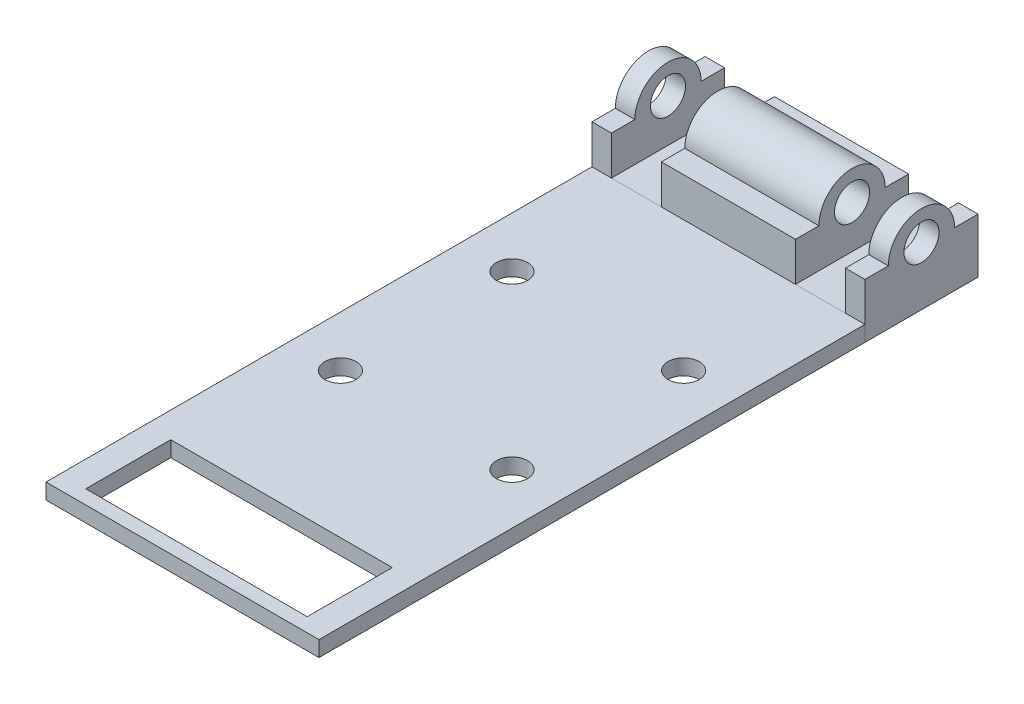
SolidWorks part; units mm, degrees
ref_plane "Front Plane" through (0, 0, 0) normal (0, 0, 1) x (1, 0, 0)
ref_plane "Top Plane" through (0, 0, 0) normal (0, 1, 0) x (1, 0, 0)
ref_plane "Right Plane" through (0, 0, 0) normal (1, 0, 0) x (0, 0, -1)
sketch "Sketch1" plane through (0, 0, 0) normal (1, 0, 0) x (0, 0, -1)
  line L0 (2.25, 1.5) -> (7.25, 1.5)
  line L1 (-2.25, -1.5) -> (2.25, -1.5)
  line L2 (-2.25, -1.5) -> (-2.25, 1.5)
  line L3 (-2.25, 1.5) -> (2.25, 1.5) construction
  line L4 (2.25, -1.5) -> (2.25, 1.5)
  line L5 (-2.25, -1.5) -> (2.25, 1.5) construction
  line L6 (-2.25, 1.5) -> (2.25, -1.5) construction
  line L7 (7.25, 1.5) -> (7.25, 8.5)
  line L8 (7.25, 8.5) -> (4.25, 8.5)
  line L9 (-2.25, 1.5) -> (-7.25, 1.5)
  line L10 (-7.25, 1.5) -> (-7.25, 8.5)
  line L11 (-7.25, 8.5) -> (-4.25, 8.5)
  line L12 (0, 1.5) -> (0, 9) construction
  line L13 (0, 11.25) -> (0, 12.75) construction
  circle A0 centre (0, 9) radius 2.25
  arc A1 (-4.25, 8.5) -> (4.25, 8.5) centre (0, 8.5) cw
  point P0 (0, 0)
  dimension "D10" = 4.5
  dimension "D11" = 1.5
  dimension "D1" = 3
  dimension "D2" = 4.5
  dimension "D3" = 5
  dimension "D4" = 5
  dimension "D5" = 7
  dimension "D6" = 7
  dimension "D7" = 3
  dimension "D8" = 3
  dimension "D9" = 7.5
extrude "Boss-Extrude1" add sketch "Sketch1" along normal mid plane 40
sketch "Sketch2" plane through (0, 0, 7.25) normal (0, 0, 1) x (1, 0, 0)
  line L0 (20, 12.75) -> (-20, 12.75) construction
  line L1 (-15, 12.75) -> (15, 12.75)
  line L2 (-15, 12.75) -> (-15, 3.5)
  line L3 (-15, 3.5) -> (15, 3.5)
  line L4 (15, 12.75) -> (15, 3.5)
  line L5 (-15, 12.75) -> (15, 3.5) construction
  line L6 (-15, 3.5) -> (15, 12.75) construction
  line L7 (20, 1.5) -> (-20, 1.5) construction
  line L8 (-20, 12.75) -> (-20, 8.5) construction
  line L9 (20, 8.5) -> (20, 12.75) construction
  point P4 (0, 8.125)
  dimension "D1" = 2
  dimension "D2" = 5
  dimension "D3" = 5
extrude "Cut-Extrude1" cut sketch "Sketch2" against normal through all
sketch "Sketch3" plane through (0, 0, 7.25) normal (0, 0, 1) x (1, 0, 0)
  line L1 (-20, 12.75) -> (-17.5, 12.75)
  line L2 (-20, 12.75) -> (-20, -1.5)
  line L3 (-20, -1.5) -> (-17.5, -1.5)
  line L4 (-17.5, 12.75) -> (-17.5, -1.5)
  line L5 (-20, 12.75) -> (-17.5, -1.5) construction
  line L6 (-20, -1.5) -> (-17.5, 12.75) construction
  line L7 (20, 12.75) -> (17.5, 12.75)
  line L8 (20, 12.75) -> (20, -1.5)
  line L9 (20, -1.5) -> (17.5, -1.5)
  line L10 (17.5, 12.75) -> (17.5, -1.5)
  line L11 (20, 12.75) -> (17.5, -1.5) construction
  line L12 (20, -1.5) -> (17.5, 12.75) construction
  line L13 (-15, 8.5) -> (-15, 12.75) construction
  line L14 (15, 12.75) -> (15, 8.5) construction
  line L15 (20, -1.5) -> (-20, -1.5) construction
  point P4 (-18.75, 5.625)
  point P10 (18.75, 5.625)
  dimension "D1" = 2.5
  dimension "D2" = 2.5
extrude "Cut-Extrude2" cut sketch "Sketch3" against normal through all
sketch "Sketch5" plane through (0, 0, 0) normal (1, 0, 0) x (0, 0, -1)
  line L5 (-4.25, 8.5) -> (-7.25, 8.5)
  line L6 (-7.25, 8.5) -> (-7.25, 3.5)
  line L7 (-7.25, 3.5) -> (7.25, 3.5)
  line L8 (7.25, 3.5) -> (7.25, 8.5)
  line L9 (7.25, 8.5) -> (4.25, 8.5)
  line L10 (-4.25, 8.5) -> (-7.25, 8.5)
  line L11 (-7.25, 8.5) -> (-7.25, 3.5)
  line L12 (-7.25, 3.5) -> (7.25, 3.5)
  line L13 (7.25, 3.5) -> (7.25, 8.5)
  line L14 (7.25, 8.5) -> (4.25, 8.5)
  circle A1 centre (0, 9) radius 2.25
  circle A2 centre (0, 9) radius 2.25
  arc A3 (4.25, 8.5) -> (-4.25, 8.5) centre (0, 8.5) ccw
  arc A4 (4.25, 8.5) -> (-4.25, 8.5) centre (0, 8.5) ccw
  dimension "D1" = 0
  dimension "D2" = 0
extrude "Boss-Extrude2" add sketch "Sketch5" against normal offset from surface 6.4 and the other way offset from surface (8.6 mm away) 6.4 up to face at (-15, 6.75, 0) other way up to face at (15, 9, -2.25)
sketch "Sketch6" plane through (-17.5, 0, 0) normal (-1, 0, 0) x (0, 0, 1)
  line L1 (-2.25, -1.5) -> (2.25, -1.5)
  line L2 (-2.25, -1.5) -> (-2.25, 1.5)
  line L3 (-2.25, 1.5) -> (2.25, 1.5)
  line L4 (2.25, -1.5) -> (2.25, 1.5)
  line L5 (-2.25, -1.5) -> (2.25, 1.5) construction
  line L6 (-2.25, 1.5) -> (2.25, -1.5) construction
  point P4 (0, 0)
extrude "Cut-Extrude4" cut sketch "Sketch6" against normal through all
sketch "Sketch8" plane through (0, 1.5, 0) normal (0, -1, 0) x (1, 0, 0)
  line L0 (-11, -60.5) -> (-11, -38.5) construction
  line L1 (0, -49.5) -> (0, -38.5) construction
  line L2 (0, -38.5) -> (-11, -38.5) construction
  line L7 (17.5, -77.25) -> (17.5, -7.25)
  line L8 (17.5, -7.25) -> (-17.5, -7.25)
  line L9 (-17.5, -7.25) -> (-17.5, -77.25)
  line L10 (17.5, -77.25) -> (-17.5, -77.25)
  line L11 (0, -49.5) -> (0, -7.25) construction
  line L12 (-17.5, 7.25) -> (-17.5, -7.25) construction
  line L13 (17.5, 7.25) -> (-17.5, 7.25) construction
  line L14 (-11, -38.5) -> (11, -38.5) construction
  line L15 (11, -38.5) -> (11, -60.5) construction
  line L16 (11, -60.5) -> (-11, -60.5) construction
  line L17 (17.5, -7.25) -> (-17.5, -7.25) construction
  circle A4 centre (-11, -38.5) radius 2.15
  circle A5 centre (-11, -60.5) radius 2.15
  circle A6 centre (-11, -38.5) radius 2.15
  circle A7 centre (11, -38.5) radius 2.15
  circle A8 centre (11, -60.5) radius 2.15
  dimension "D2" = 4.3
  dimension "D15" = 11
  dimension "D16" = 11
  dimension "D17" = 11
  dimension "D8" = 17.5
  dimension "D9" = 4.3
  dimension "D10" = 4.3
  dimension "D11" = 4.3
  dimension "D21" = 4.3
  dimension "D1" = 11
  dimension "D3" = 11
  dimension "D4" = 35
  dimension "D5" = 11
  dimension "D6" = 70
  dimension "D7" = 42.25
  dimension "D12" = 90
  dimension "D13" = 11
  dimension "D14" = 11
  dimension "D18" = 90
  dimension "D20" = 90
sketch "Sketch9" plane through (0, 1.5, 0) normal (0, -1, 0) x (1, 0, 0)
  line L0 (-17.5, 0) -> (17.5, 0) construction
  line L1 (-17.5, 7.25) -> (-17.5, -7.25) construction
  line L2 (17.5, -7.25) -> (17.5, 7.25) construction
  line L3 (-17.5, 77.25) -> (17.5, 77.25)
  line L4 (17.5, -77.25) -> (17.5, -7.25)
  line L5 (17.5, -7.25) -> (-17.5, -7.25)
  line L6 (-17.5, -7.25) -> (-17.5, -77.25)
  line L7 (-17.5, -77.25) -> (17.5, -77.25)
  line L8 (17.5, -77.25) -> (17.5, -7.25)
  line L9 (17.5, -7.25) -> (-17.5, -7.25)
  line L10 (-17.5, -7.25) -> (-17.5, -77.25)
  line L11 (-17.5, -77.25) -> (17.5, -77.25)
  line L12 (-17.5, 7.25) -> (-17.5, 77.25)
  line L13 (17.5, 7.25) -> (-17.5, 7.25)
  line L14 (17.5, 77.25) -> (17.5, 7.25)
  dimension "D5" = 0
extrude "Boss-Extrude4" add sketch "Sketch9" against normal blind 2 separate body
sketch "Sketch10" plane through (0, 3.5, 0) normal (0, 1, 0) x (1, 0, 0)
  line L0 (-14, -77.25) -> (-14, -75.25) construction
  line L1 (-17.5, -77.25) -> (17.5, -77.25) construction
  line L2 (-14, -75.25) -> (-17.5, -75.25) construction
  line L3 (-17.5, -7.25) -> (-17.5, -77.25) construction
  line L4 (-14.2, -64.55) -> (14.2, -64.55)
  line L5 (-14, -75.25) -> (14, -75.25) construction
  line L6 (-14, -75.25) -> (-14, -64.75) construction
  line L7 (-14, -64.75) -> (14, -64.75) construction
  line L8 (14, -75.25) -> (14, -64.75) construction
  line L9 (-14, -75.25) -> (14, -64.75) construction
  line L10 (-14, -64.75) -> (14, -75.25) construction
  line L11 (14.2, -75.45) -> (14.2, -64.55)
  line L12 (-14.2, -75.45) -> (14.2, -75.45)
  line L13 (-14.2, -75.45) -> (-14.2, -64.55)
  point P10 (0, -70)
  dimension "D1" = 28
  dimension "D2" = 10.5
  dimension "D3" = 2
  dimension "D4" = 3.5
  dimension "D5" = 0.2
extrude "Cut-Extrude5" cut sketch "Sketch10" against normal through all
sketch "Sketch13" plane through (0, 3.5, 0) normal (0, 1, 0) x (1, 0, 0)
  line L0 (-11, -24) -> (11, -24) construction
  line L1 (11, -24) -> (11, -46) construction
  line L2 (11, -46) -> (-11, -46) construction
  line L3 (-11, -46) -> (-11, -24) construction
  line L4 (17.5, -7.25) -> (-17.5, -7.25) construction
  line L5 (-17.5, -7.25) -> (-17.5, -77.25) construction
  circle A0 centre (-11, -46) radius 2
  circle A1 centre (11, -46) radius 2
  circle A2 centre (11, -24) radius 2
  circle A3 centre (-11, -24) radius 2
  dimension "D1" = 22
  dimension "D2" = 22
  dimension "D3" = 16.75
  dimension "D4" = 6.5
extrude "Cut-Extrude6" cut sketch "Sketch13" against normal through all
